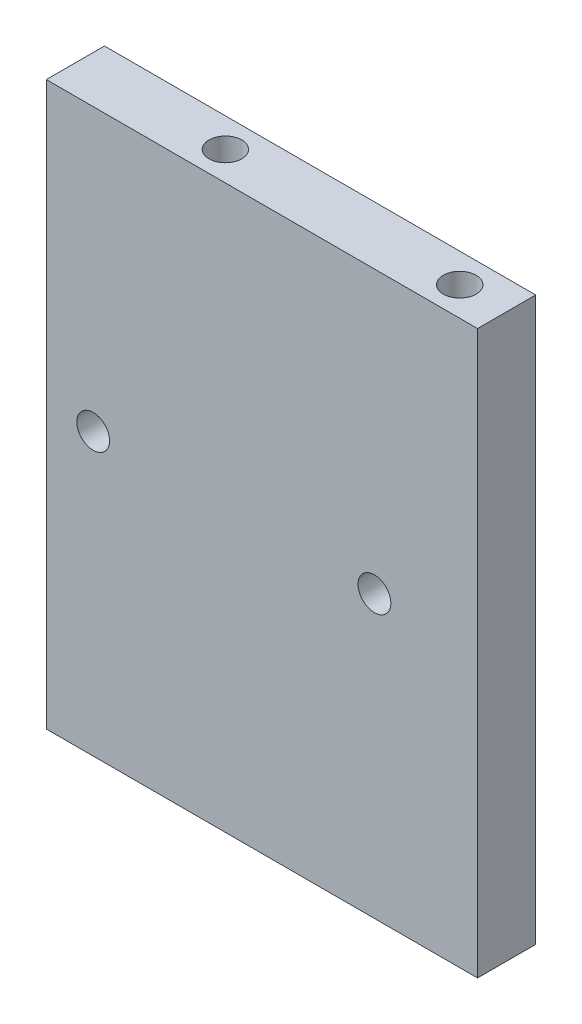
SolidWorks part; units mm, degrees
material "6061 Alloy"
ref_plane "Front Plane" through (0, 0, 0) normal (0, 0, 1) x (1, 0, 0)
ref_plane "Top Plane" through (0, 0, 0) normal (0, 1, 0) x (1, 0, 0)
ref_plane "Right Plane" through (0, 0, 0) normal (1, 0, 0) x (0, 0, -1)
sketch "Sketch1" plane through (0, 0, 0) normal (0, 0, 1) x (1, 0, 0)
  line L1 (-23, 30) -> (23, 30)
  line L2 (-23, 30) -> (-23, -30)
  line L3 (-23, -30) -> (23, -30)
  line L4 (23, 30) -> (23, -30)
  line L5 (0, -30) -> (0, 30) construction
  line L6 (-23, 0) -> (23, 0) construction
  point P0 (0, 0)
  dimension "D1" = 60
  dimension "D2" = 46
extrude "1/4" add sketch "Sketch1" along normal blind 6.2
sketch "Sketch2" plane through (0, 0, 0) normal (0, 0, 1) x (1, 0, 0)
  line L0 (0, 0) -> (-18, 0) construction
  line L1 (0, 0) -> (0, 8.9877) construction
  line L2 (-23, 30) -> (-23, -30) construction
  circle A0 centre (-18, 0) radius 1.75
  circle A2 centre (12, 0) radius 1.75
  dimension "D2" = 3.5
  dimension "D1" = 5
  dimension "D3" = 2
extrude "M4_DRILL" cut sketch "Sketch2" along normal up to surface (6.2 mm away) up to face at (0, 0, 6.2)
sketch "Sketch3" plane through (0, -30, 0) normal (0, -1, 0) x (1, 0, 0)
  line L0 (-23, 3.1) -> (-7, 3.1) construction
  line L1 (-23, 6.2) -> (-23, 0) construction
  circle A0 centre (-7, 3.1) radius 1.75
  circle A1 centre (18, 3.1) radius 1.75
  dimension "D1" = 3.5
  dimension "D2" = 16
  dimension "D4" = 25
  dimension "D3" = 2
extrude "M4_DRILL2" cut sketch "Sketch3" against normal blind 8
sketch "Sketch4" plane through (0, 30, 0) normal (0, 1, 0) x (1, 0, 0)
  circle A0 centre (18, -3.1) radius 1.75 construction
  circle A1 centre (-7, -3.1) radius 1.75 construction
  circle A2 centre (18, -3.1) radius 1.75
  circle A3 centre (-7, -3.1) radius 1.75
extrude "M4_DRILL3" cut sketch "Sketch4" against normal blind 8
